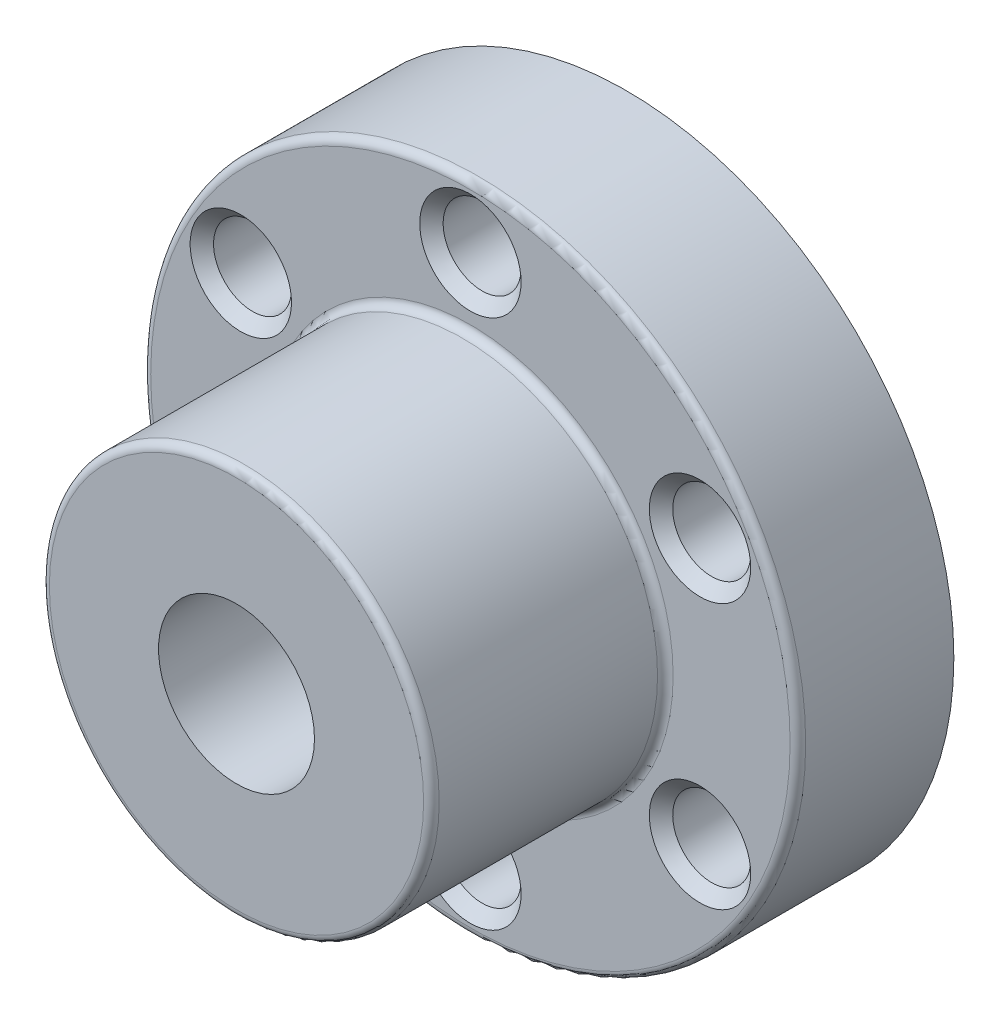
SolidWorks part; units mm, degrees
material "ABS"
ref_plane "Front Plane" through (0, 0, 0) normal (0, 0, 1) x (1, 0, 0)
ref_plane "Top Plane" through (0, 0, 0) normal (0, 1, 0) x (1, 0, 0)
ref_plane "Right Plane" through (0, 0, 0) normal (1, 0, 0) x (0, 0, -1)
sketch "Sketch1" plane through (0, 0, 0) normal (0, 0, 1) x (1, 0, 0)
  circle A0 centre (0, 0) radius 21
  dimension "D1" = 42
extrude "Boss-Extrude1" add sketch "Sketch1" along normal blind 10
sketch "Sketch2" plane through (0, 0, 10) normal (0, 0, 1) x (1, 0, 0)
  circle A0 centre (0, 0) radius 12.5
  dimension "D1" = 25
extrude "Boss-Extrude2" add sketch "Sketch2" along normal blind 15
sketch "Sketch3" plane through (0, 0, 25) normal (0, 0, 1) x (1, 0, 0)
  circle A0 centre (0, 0) radius 5
  dimension "D1" = 10
extrude "Cut-Extrude1" cut sketch "Sketch3" against normal through all
sketch "Sketch4" plane through (0, 0, 0) normal (0, 0, -1) x (-1, 0, 0)
  circle A0 centre (0, 0) radius 17 construction
  circle A1 centre (0, 17) radius 2.5
  dimension "D1" = 34
  dimension "D2" = 5
extrude "Cut-Extrude2" cut sketch "Sketch4" against normal through all
fillet "Fillet1" radius 0.5 3 edges at (21, 0, 10) (12.5, 0, 10) (12.5, 0, 25)
chamfer "Chamfer2" distance 0.75 angle 45 1 edges at (2.5, 17, 10)
pattern_circular "CirPattern2" count 6 over 360 about axis through (0, 0, 0) along (0, 0, 1) of "Chamfer2", "Cut-Extrude2"
